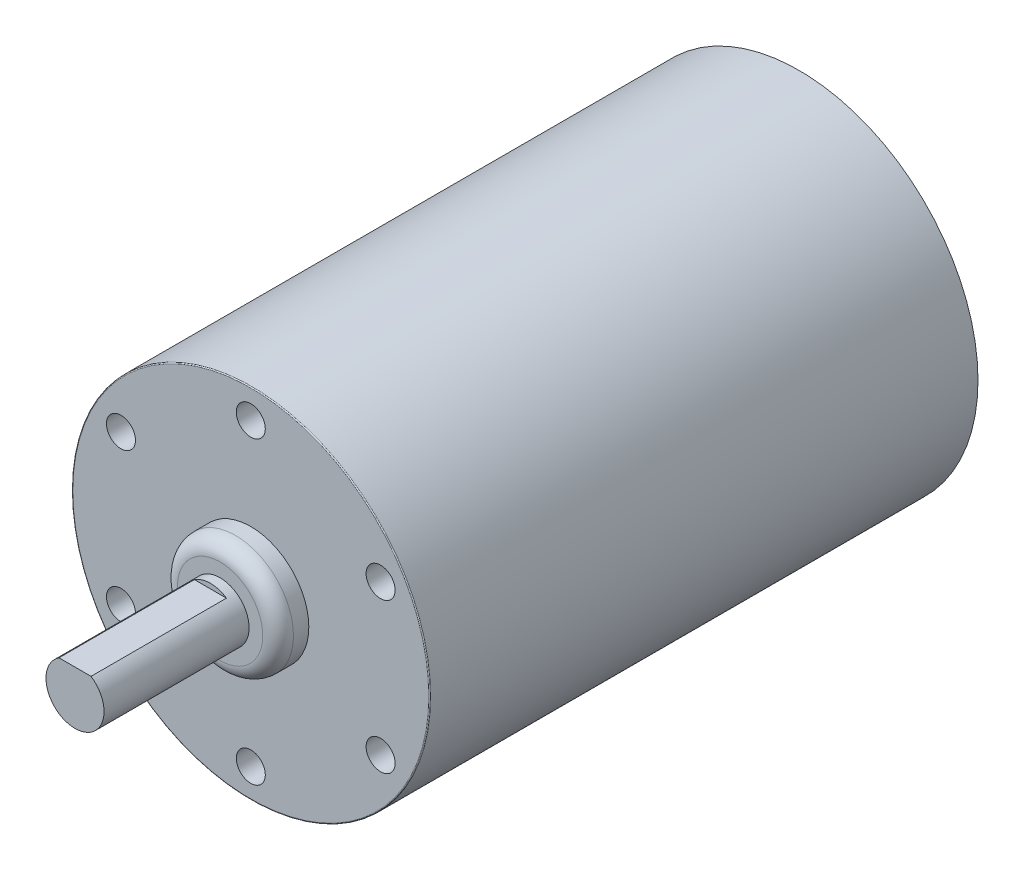
SolidWorks part; units mm, degrees
ref_plane "Front Plane" through (0, 0, 0) normal (0, 0, 1) x (1, 0, 0)
ref_plane "Top Plane" through (0, 0, 0) normal (0, 1, 0) x (1, 0, 0)
ref_plane "Right Plane" through (0, 0, 0) normal (1, 0, 0) x (0, 0, -1)
sketch "Sketch1" plane through (0, 0, 0) normal (0, 0, 1) x (1, 0, 0)
  circle A0 centre (0, 0) radius 18.5
  dimension "D1" = 37
extrude "Boss-Extrude1" add sketch "Sketch1" along normal blind 56.6928
fillet "Fillet3" radius 0.1 1 edges at (18.5, 0, 56.6928)
sketch "Sketch2" plane through (0, 0, 56.6928) normal (0, 0, 1) x (1, 0, 0)
  circle A0 centre (0, 0) radius 6
  dimension "D1" = 12
extrude "Boss-Extrude2" add sketch "Sketch2" along normal blind 3.175
fillet "Fillet2" radius 1.5875 1 edges at (6, 0, 59.8678)
sketch "Sketch5" plane through (0, 0, 59.8678) normal (0, 0, 1) x (1, 0, 0)
  circle A0 centre (0, 0) radius 3
  dimension "D1" = 6
extrude "Boss-Extrude3" add sketch "Sketch5" along normal blind 15
sketch "Sketch6" plane through (0, 0, 74.8678) normal (0, 0, 1) x (1, 0, 0)
  line L0 (-1.6583, 2.5) -> (1.6583, 2.5)
  circle A0 centre (0, 0) radius 3 construction
  circle A1 centre (0, 0) radius 3 construction
  arc A2 (-1.6583, 2.5) -> (1.6583, 2.5) centre (0, 0) cw
  point P7 (0, -3)
  dimension "D1" = 5.5
extrude "Cut-Extrude1" cut sketch "Sketch6" against normal blind 14
sketch "Sketch7" plane through (0, 0, 56.6928) normal (0, 0, 1) x (1, 0, 0)
  circle A0 centre (0, 0) radius 15.5 construction
  circle A1 centre (0, 15.5) radius 1.5
  circle A2 centre (0, 0) radius 18.5 construction
  circle A3 centre (13.4234, 7.75) radius 1.5
  circle A4 centre (13.4234, -7.75) radius 1.5
  circle A5 centre (0, -15.5) radius 1.5
  circle A6 centre (-13.4234, -7.75) radius 1.5
  circle A7 centre (-13.4234, 7.75) radius 1.5
  point P6 (0, 17)
  point P8 (0, 18.5)
  point P22 (0, 0)
  dimension "D1" = 31
  dimension "D2" = 3
  dimension "D3" = 6
extrude "Cut-Extrude2" cut sketch "Sketch7" against normal blind 10
